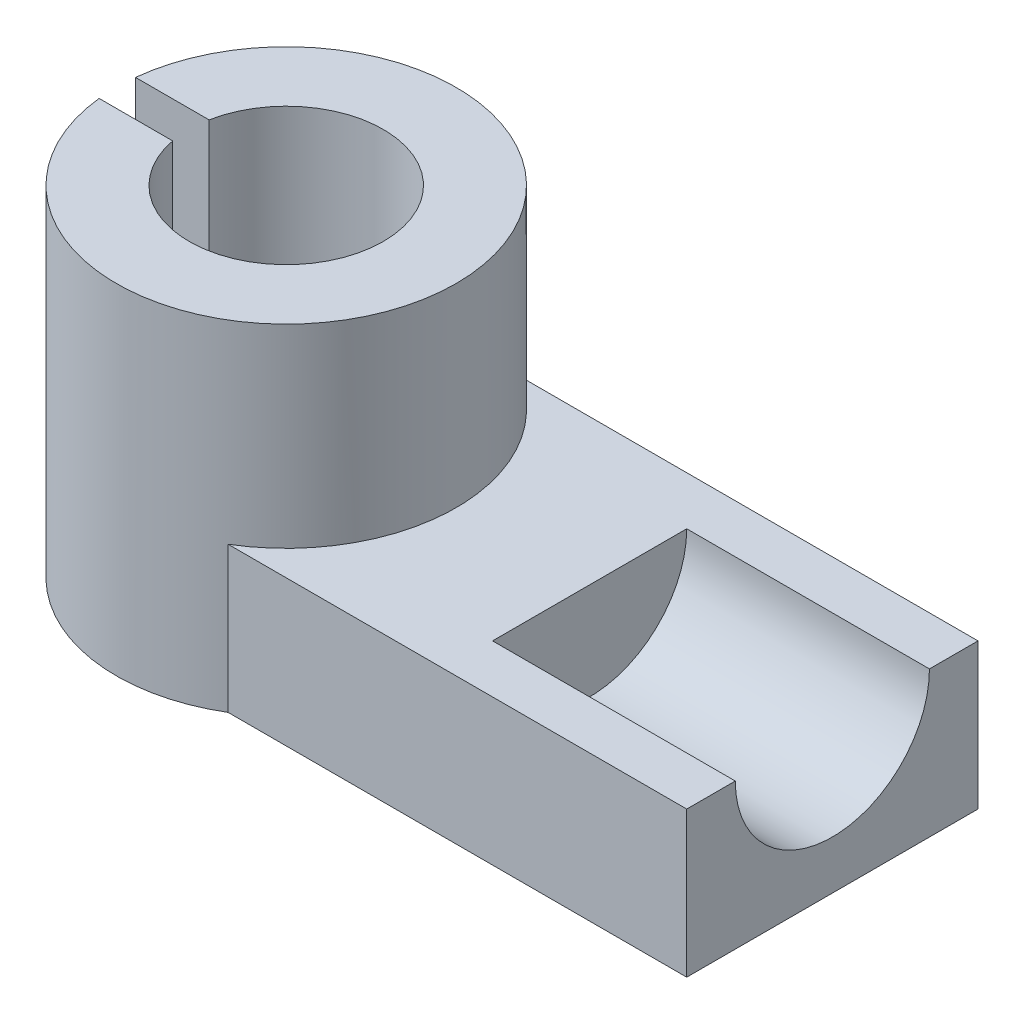
SolidWorks part; units mm, degrees
ref_plane "Front Plane" through (0, 0, 0) normal (0, 0, 1) x (1, 0, 0)
ref_plane "Top Plane" through (0, 0, 0) normal (0, 1, 0) x (1, 0, 0)
ref_plane "Right Plane" through (0, 0, 0) normal (1, 0, 0) x (0, 0, -1)
sketch "Sketch1" plane through (0, 0, 0) normal (0, 1, 0) x (1, 0, 0)
  line L0 (0, 0) -> (228.6, 0) construction
  line L1 (228.6, 60.96) -> (228.6, -60.96)
  line L2 (228.6, -60.96) -> (36.6324, -60.96)
  line L3 (228.6, 60.96) -> (36.6324, 60.96)
  arc A1 (36.6324, -60.96) -> (36.6324, 60.96) centre (0, 0) cw
  dimension "D1" = 71.12
  dimension "D2" = 228.6
  dimension "D3" = 121.92
extrude "Boss-Extrude2" add sketch "Sketch1" along normal blind 60.96
sketch "Sketch2" plane through (0, 60.96, 0) normal (0, 1, 0) x (1, 0, 0)
  circle A0 centre (0, 0) radius 71.12
  dimension "D1" = 142.24
extrude "Boss-Extrude3" add sketch "Sketch2" along normal blind 81.28
sketch "Sketch3" plane through (228.6, 0, 0) normal (1, 0, 0) x (0, 0, -1)
  line L0 (60.96, 60.96) -> (-60.96, 60.96) construction
  line L1 (-40.64, 60.96) -> (40.64, 60.96)
  line L2 (40.64, 60.96) -> (60.96, 60.96)
  arc A0 (40.64, 60.96) -> (-40.64, 60.96) centre (0, 60.96) cw
  line M4 (60.96, 60.96) -> (-60.96, 60.96)
  dimension "D1" = 40.64
  dimension "D2" = 20.32
extrude "Cut-Extrude1" cut sketch "Sketch3" against normal blind 101.6 contours A0 M4
sketch "Sketch4" plane through (0, 142.24, 0) normal (0, 1, 0) x (1, 0, 0)
  line L0 (0, 0) -> (-71.12, 0) construction
  line L1 (0, 71.12) -> (0, -71.12) construction
  line L2 (-39.9192, 7.62) -> (-70.7106, 7.62)
  line L3 (-39.9192, -7.62) -> (-70.7106, -7.62)
  circle A1 centre (0, 0) radius 71.12 construction
  arc A2 (-39.9192, 7.62) -> (-39.9192, -7.62) centre (0, 0) cw
  arc A3 (-70.7106, -7.62) -> (-70.7106, 7.62) centre (0, 0) cw
  point P13 (0, 0)
  dimension "D1" = 40.64
  dimension "D2" = 7.62
extrude "Cut-Extrude2" cut sketch "Sketch4" against normal blind 142.24
